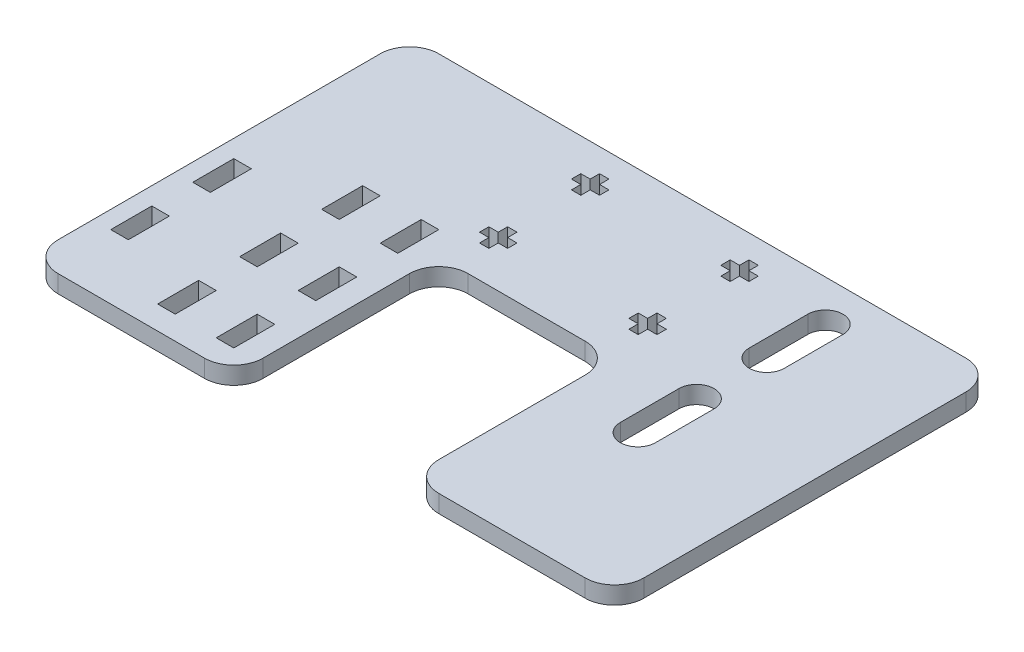
SolidWorks part; units mm, degrees
ref_plane "Front Plane" through (0, 0, 0) normal (0, 0, 1) x (1, 0, 0)
ref_plane "Top Plane" through (0, 0, 0) normal (0, 1, 0) x (1, 0, 0)
ref_plane "Right Plane" through (0, 0, 0) normal (1, 0, 0) x (0, 0, -1)
sketch "Sketch1" plane through (0, 0, 0) normal (0, 1, 0) x (1, 0, 0)
  line L1 (50, -32.5) -> (-50, -32.5)
  line L2 (50, -32.5) -> (50, 32.5)
  line L3 (50, 32.5) -> (-50, 32.5)
  line L4 (-50, -32.5) -> (-50, 32.5)
  line L5 (50, -32.5) -> (-50, 32.5) construction
  line L6 (50, 32.5) -> (-50, -32.5) construction
  line L7 (-15, 2.5) -> (15, 2.5)
  line L8 (-15, 2.5) -> (-15, -32.5)
  line L9 (-15, -32.5) -> (15, -32.5)
  line L10 (15, 2.5) -> (15, -32.5)
  line L11 (-15, 2.5) -> (15, -32.5) construction
  line L12 (-15, -32.5) -> (15, 2.5) construction
  point P0 (0, 0)
  point P6 (0, -15)
  dimension "D1" = 65
  dimension "D2" = 100
  dimension "D3" = 35
  dimension "D4" = 30
  dimension "D5" = 35
extrude "Boss-Extrude1" add sketch "Sketch1" along normal blind 3 contours L7 L10 L1 L2 L3 L4 L8
fillet "Fillet1" radius 5 1 edges at (-15, 1.5, -2.5)
fillet "Fillet2" radius 5 1 edges at (15, 1.5, -2.5)
sketch "Sketch2" plane through (0, 3, 0) normal (0, 1, 0) x (1, 0, 0)
  line L0 (-15, -2.5) -> (-15, -32.5) construction
  line L1 (-22, 6.5) -> (-19, 6.5)
  line L2 (-22, 6.5) -> (-22, -0.5)
  line L3 (-22, -0.5) -> (-19, -0.5)
  line L4 (-19, 6.5) -> (-19, -0.5)
  line L5 (-22, 6.5) -> (-19, -0.5) construction
  line L6 (-22, -0.5) -> (-19, 6.5) construction
  line L7 (-15, -32.5) -> (-50, -32.5) construction
  point P0 (-20.5, 3)
  dimension "D1" = 3
  dimension "D2" = 7
  dimension "D3" = 4
  dimension "D4" = 32
extrude "Cut-Extrude1" cut sketch "Sketch2" against normal blind 3
pattern_linear "LPattern1" count 3 spacing 14 along (0, 0, 1) count 2 spacing 10 along (-1, 0, 0) of "Cut-Extrude1"
sketch "Sketch3" plane through (0, 3, 0) normal (0, 1, 0) x (1, 0, 0)
  line L0 (50, 32.5) -> (-50, 32.5) construction
  line L1 (-13.55, 28.5) -> (-11.95, 28.5)
  line L2 (-13.55, 28.5) -> (-13.55, 26.9)
  line L3 (-13.55, 23.7) -> (-11.95, 23.7)
  line L4 (-11.95, 28.5) -> (-11.95, 26.9)
  line L5 (-50, -32.5) -> (-50, 32.5) construction
  line L7 (-15.15, 26.9) -> (-13.55, 26.9)
  line L8 (-15.15, 26.9) -> (-15.15, 25.3)
  line L9 (-15.15, 25.3) -> (-13.55, 25.3)
  line L10 (-10.35, 26.9) -> (-10.35, 25.3)
  line L14 (-11.95, 26.9) -> (-10.35, 26.9)
  line L17 (-11.95, 25.3) -> (-11.95, 23.7)
  line L18 (-11.95, 25.3) -> (-10.35, 25.3)
  line L19 (-13.55, 25.3) -> (-13.55, 23.7)
  point P0 (0, 0)
  point P5 (0, 0)
  dimension "D1" = 1.6
  dimension "D2" = 4.8
  dimension "D3" = 4.8
  dimension "D4" = 1.6
  dimension "D5" = 4
  dimension "D6" = 34.85
  dimension "D7" = 1.6
  dimension "D8" = 1.6
extrude "Cut-Extrude2" cut sketch "Sketch3" against normal blind 3
pattern_linear "LPattern2" count 2 spacing 25.5 along (1, 0, 0) count 2 spacing 15.7 along (0, 0, 1) of "Cut-Extrude2"
fillet "Fillet3" radius 5 1 edges at (-50, 1.5, -32.5)
fillet "Fillet4" radius 5 1 edges at (50, 1.5, -32.5)
fillet "Fillet5" radius 5 1 edges at (-50, 1.5, 32.5)
fillet "Fillet6" radius 5 1 edges at (50, 1.5, 32.5)
fillet "Fillet7" radius 5 1 edges at (15, 1.5, 32.5)
fillet "Fillet8" radius 5 1 edges at (-15, 1.5, 32.5)
sketch "Sketch4" plane through (0, 3, 0) normal (0, 1, 0) x (1, 0, 0)
  line L0 (28, 25.5) -> (28, 15.5) construction
  line L1 (31, 25.5) -> (31, 15.5)
  line L2 (25, 25.5) -> (25, 15.5)
  line L3 (50, -27.5) -> (50, 27.5) construction
  line L4 (45, -32.5) -> (20, -32.5) construction
  arc A0 (31, 25.5) -> (25, 25.5) centre (28, 25.5) ccw
  arc A1 (25, 15.5) -> (31, 15.5) centre (28, 15.5) ccw
  point P2 (28, 20.5)
  dimension "D2" = 3
  dimension "D1" = 10
  dimension "D3" = 19
  dimension "D4" = 48
extrude "Cut-Extrude3" cut sketch "Sketch4" against normal blind 3
pattern_linear "LPattern3" count 2 spacing 22 along (0, 0, 1) of "Cut-Extrude3"
sketch "Sketch5" plane through (0, 3, 0) normal (0, 1, 0) x (1, 0, 0)
  line L0 (-29, 6.5) -> (-32, 6.5) construction
  line L1 (-47, -0.5) -> (-44, -0.5)
  line L2 (-47, -0.5) -> (-47, -7.5)
  line L3 (-47, -7.5) -> (-44, -7.5)
  line L4 (-44, -0.5) -> (-44, -7.5)
  line L5 (-50, -27.5) -> (-50, 27.5) construction
  point P4 (-30.5, 6.5)
  dimension "D1" = 3
  dimension "D2" = 7
  dimension "D3" = 7
  dimension "D4" = 3
extrude "Cut-Extrude4" cut sketch "Sketch5" against normal blind 3
pattern_linear "LPattern4" count 2 spacing 14 along (0, 0, 1) of "Cut-Extrude4"
